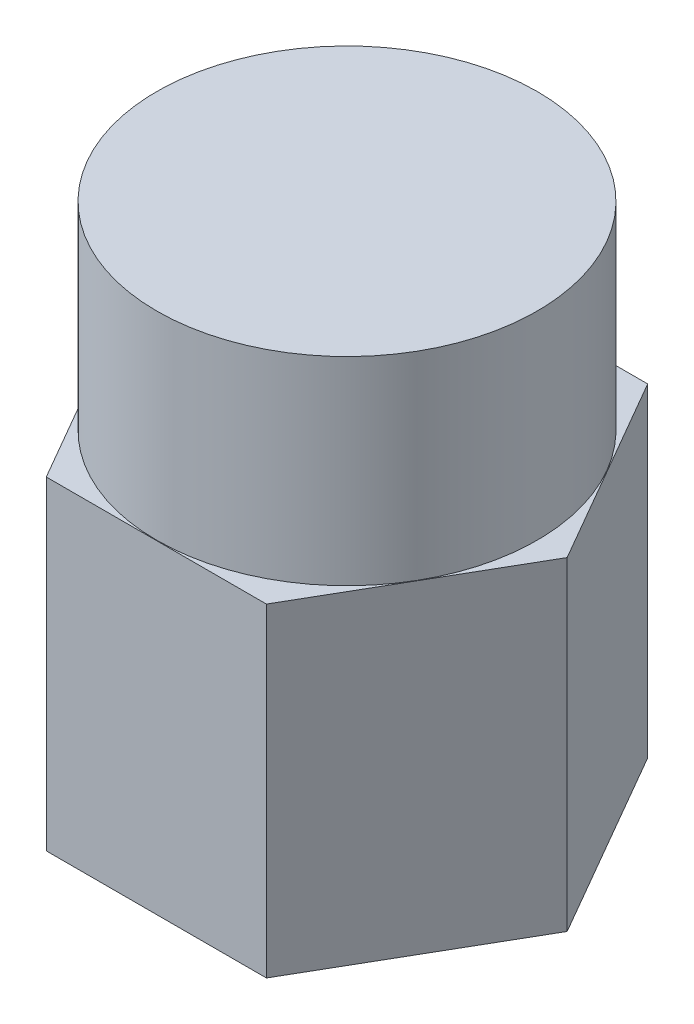
SolidWorks part; units mm, degrees
ref_plane "Front Plane" through (0, 0, 0) normal (0, 0, 1) x (1, 0, 0)
ref_plane "Top Plane" through (0, 0, 0) normal (0, 1, 0) x (1, 0, 0)
ref_plane "Right Plane" through (0, 0, 0) normal (1, 0, 0) x (0, 0, -1)
sketch "Sketch1" plane through (0, 0, 0) normal (0, 1, 0) x (1, 0, 0)
  line L1 (12.644, 0) -> (6.322, 10.95)
  line L2 (6.322, 10.95) -> (-6.322, 10.95)
  line L3 (-6.322, 10.95) -> (-12.644, 0)
  line L4 (-12.644, 0) -> (-6.322, -10.95)
  line L5 (-6.322, -10.95) -> (6.322, -10.95)
  line L6 (6.322, -10.95) -> (12.644, 0)
  circle A0 centre (0, 0) radius 10.95 construction
  dimension "D1" = 21.9
extrude "Boss-Extrude1" add sketch "Sketch1" along normal blind 18.6
sketch "Sketch2" plane through (0, 18.6, 0) normal (0, 1, 0) x (1, 0, 0)
  circle A0 centre (0, 0) radius 10.925
  dimension "D1" = 21.85
extrude "Boss-Extrude2" add sketch "Sketch2" along normal blind 11.4
